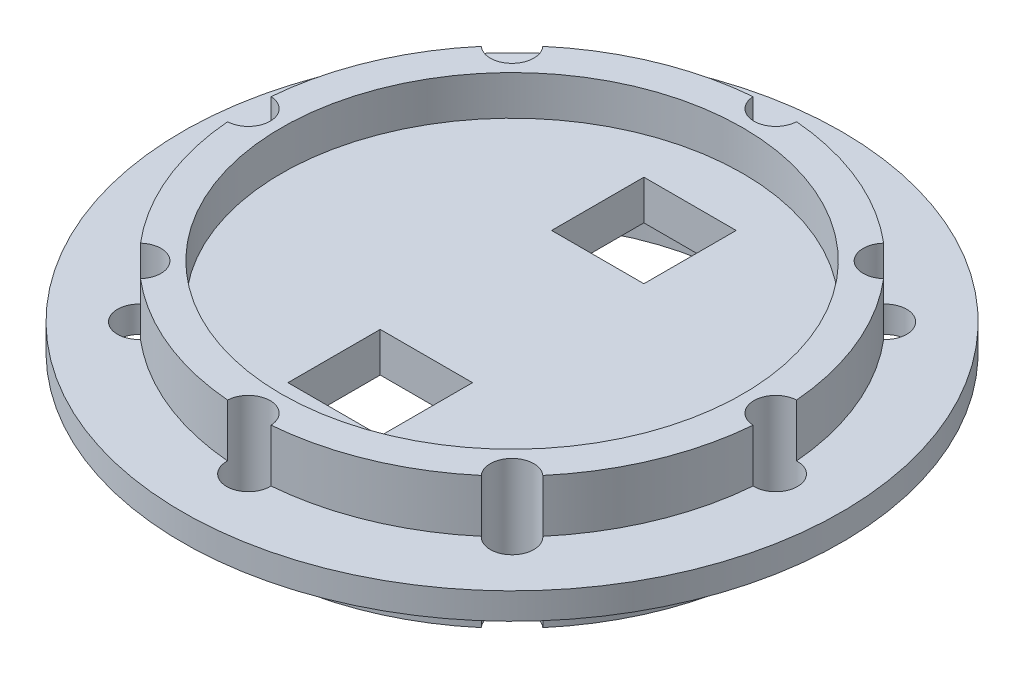
SolidWorks part; units mm, degrees
ref_plane "Front Plane" through (0, 0, 0) normal (0, 0, 1) x (1, 0, 0)
ref_plane "Top Plane" through (0, 0, 0) normal (0, 1, 0) x (1, 0, 0)
ref_plane "Right Plane" through (0, 0, 0) normal (1, 0, 0) x (0, 0, -1)
sketch "Sketch1" plane through (0, 0, 0) normal (0, 1, 0) x (1, 0, 0)
  circle A0 centre (0, 0) radius 20
  dimension "D1" = 40
extrude "Boss-Extrude1" add sketch "Sketch1" along normal blind 4
sketch "Sketch2" plane through (0, 4, 0) normal (0, 1, 0) x (1, 0, 0)
  circle A0 centre (0, 0) radius 20
  circle A1 centre (0, 0) radius 17.5
  dimension "D1" = 35
extrude "Boss-Extrude2" add sketch "Sketch2" along normal blind 4
sketch "Sketch3" plane through (0, 0, 0) normal (0, -1, 0) x (1, 0, 0)
  circle A0 centre (0, 0) radius 20
extrude "Cut-Extrude1" cut sketch "Sketch3" against normal blind 2
sketch "Sketch4" plane through (0, 2, 0) normal (0, -1, 0) x (-1, 0, 0)
  circle A0 centre (0, 0) radius 20
extrude "Cut-Extrude2" cut sketch "Sketch4" against normal blind 1
sketch "Sketch5" plane through (0, 3, 0) normal (0, -1, 0) x (1, 0, 0)
  circle A0 centre (0, 0) radius 25
  dimension "D1" = 50
extrude "Boss-Extrude3" add sketch "Sketch5" along normal blind 2
sketch "Sketch6" plane through (0, 1, 0) normal (0, -1, 0) x (1, 0, 0)
  circle A0 centre (0, 0) radius 17.5
  circle A1 centre (0, 0) radius 20
  dimension "D1" = 40
  dimension "D2" = 35
extrude "Boss-Extrude4" add sketch "Sketch6" along normal blind 4
sketch "Sketch7" plane through (0, -3, 0) normal (0, -1, 0) x (1, 0, 0)
  circle A0 centre (-20, 0) radius 1.5
  circle A1 centre (-14.1421, 14.1421) radius 1.5
  circle A2 centre (0, 20) radius 1.5
  circle A3 centre (14.1421, 14.1421) radius 1.5
  circle A4 centre (20, 0) radius 1.5
  circle A5 centre (14.1421, -14.1421) radius 1.5
  circle A6 centre (0, -20) radius 1.5
  circle A7 centre (-14.1421, -14.1421) radius 1.5
  dimension "D2" = 3
  dimension "D1" = 20
  dimension "D3" = 8
extrude "Cut-Extrude3" cut sketch "Sketch7" against normal blind 16
sketch "Sketch8" plane through (0, 1, 0) normal (0, -1, 0) x (1, 0, 0)
  line L0 (0, 0) -> (0, 17.5) construction
  line L1 (0, 0) -> (15.6755, 0) construction
  line L2 (-3.5, 13.5) -> (3.5, 13.5)
  line L3 (-3.5, 13.5) -> (-3.5, 6.5)
  line L4 (-3.5, 6.5) -> (3.5, 6.5)
  line L5 (3.5, 13.5) -> (3.5, 6.5)
  line L6 (-3.5, 13.5) -> (3.5, 6.5) construction
  line L7 (-3.5, 6.5) -> (3.5, 13.5) construction
  line L8 (-3.5, -6.5) -> (3.5, -6.5)
  line L9 (-3.5, -13.5) -> (-3.5, -6.5)
  line L10 (-3.5, -13.5) -> (3.5, -13.5)
  line L11 (3.5, -13.5) -> (3.5, -6.5)
  circle A0 centre (0, 0) radius 17.5 construction
  point P5 (0, 10)
  dimension "D1" = 7
  dimension "D2" = 7
  dimension "D3" = 10
extrude "Cut-Extrude4" cut sketch "Sketch8" against normal blind 2
sketch "Sketch9" plane through (0, 3, 0) normal (0, -1, 0) x (1, 0, 0)
  line L1 (3.5, 6.5) -> (-3.5, 6.5)
  line L2 (3.5, 6.5) -> (3.5, 13.5)
  line L3 (3.5, 13.5) -> (-3.5, 13.5)
  line L4 (-3.5, 6.5) -> (-3.5, 13.5)
  line L5 (-3.5, -6.5) -> (3.5, -6.5)
  line L6 (-3.5, -6.5) -> (-3.5, -13.5)
  line L7 (-3.5, -13.5) -> (3.5, -13.5)
  line L8 (3.5, -6.5) -> (3.5, -13.5)
extrude "Cut-Extrude5" cut sketch "Sketch9" against normal blind 2 contours L6 L5 L8 L7
sketch "Sketch10" plane through (0, 3, 0) normal (0, -1, 0) x (1, 0, 0)
  line L1 (3.5, 6.5) -> (-3.5, 6.5)
  line L2 (3.5, 6.5) -> (3.5, 13.5)
  line L3 (3.5, 13.5) -> (-3.5, 13.5)
  line L4 (-3.5, 6.5) -> (-3.5, 13.5)
extrude "Cut-Extrude6" cut sketch "Sketch10" against normal blind 2
sketch "Sketch11" plane through (0, 8, 0) normal (0, 1, 0) x (1, 0, 0)
  circle A0 centre (0, 0) radius 24.2537
extrude "Cut-Extrude7" cut sketch "Sketch11" against normal blind 1
sketch "Sketch12" plane through (0, 3, 0) normal (0, 1, 0) x (1, 0, 0)
  circle A0 centre (20, 0) radius 1.65
  circle A1 centre (14.1421, -14.1421) radius 1.65
  circle A2 centre (0, -20) radius 1.65
  circle A3 centre (-14.1421, -14.1421) radius 1.65
  circle A4 centre (-20, 0) radius 1.65
  circle A5 centre (-14.1421, 14.1421) radius 1.65
  circle A6 centre (0, 20) radius 1.65
  circle A7 centre (14.1421, 14.1421) radius 1.65
  dimension "D1" = 3.3
  dimension "D2" = 8
extrude "Cut-Extrude8" cut sketch "Sketch12" against normal mid plane 20
